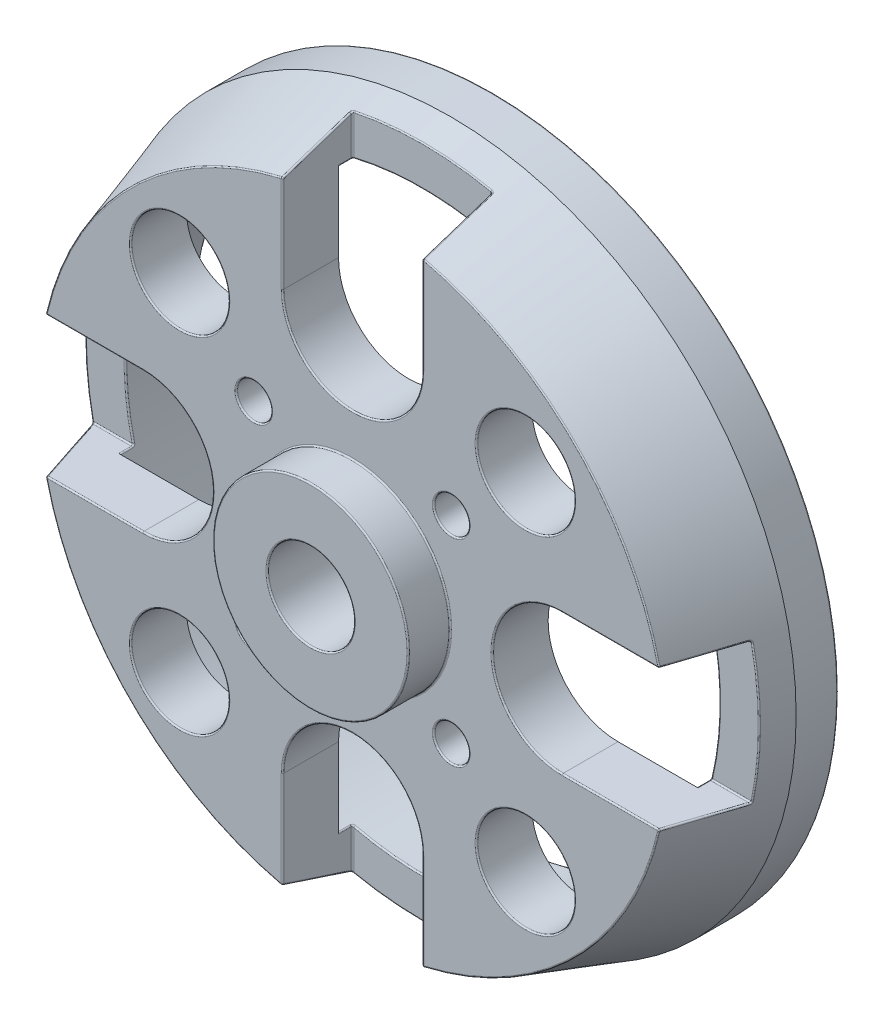
SolidWorks part; units mm, degrees
ref_plane "Спереди" through (0, 0, 0) normal (0, 0, 1) x (1, 0, 0)
ref_plane "Сверху" through (0, 0, 0) normal (0, 1, 0) x (1, 0, 0)
ref_plane "Справа" through (0, 0, 0) normal (1, 0, 0) x (0, 0, -1)
sketch "Эскиз1" plane through (0, 0, 0) normal (0, 0, 1) x (1, 0, 0)
  circle A0 centre (0, 0) radius 24.75
  dimension "D1" = 49.5
extrude "Бобышка-Вытянуть1" add sketch "Эскиз1" along normal blind 3
ref_plane "Плоскость1" through (0, 0, 10) normal (0, 0, 1) x (1, 0, 0)
sketch "Эскиз2" plane through (0, 0, 10) normal (0, 0, 1) x (1, 0, 0)
  circle A0 centre (0, 0) radius 22.5
  dimension "D1" = 45
loft "По сечениям1" add profiles "Эскиз2" section edge at (24.75, 0, 3) section "Эскиз2"
sketch "Эскиз3" plane through (0, 0, 10) normal (0, 0, 1) x (1, 0, 0)
  circle A0 centre (0, 0) radius 7
  dimension "D1" = 14
extrude "Бобышка-Вытянуть2" add sketch "Эскиз3" along normal blind 3
sketch "Эскиз4" plane through (0, 0, 10) normal (0, 0, 1) x (1, 0, 0)
  line L0 (0, 22.5) -> (0, -22.5) construction
  line L1 (-5, 15) -> (-5, 27.2025)
  line L2 (-5, 27.2025) -> (5, 27.2025)
  line L3 (5, 27.2025) -> (5, 15)
  line L4 (15, 5) -> (27.2025, 5)
  line L5 (27.2025, 5) -> (27.2025, -5)
  line L6 (27.2025, -5) -> (15, -5)
  line L7 (5, -15) -> (5, -27.2025)
  line L8 (5, -27.2025) -> (-5, -27.2025)
  line L9 (-5, -27.2025) -> (-5, -15)
  line L10 (-15, -5) -> (-27.2025, -5)
  line L11 (-27.2025, -5) -> (-27.2025, 5)
  line L12 (-27.2025, 5) -> (-15, 5)
  line L13 (-15.9099, 15.9099) -> (15.9099, -15.9099) construction
  circle A0 centre (0, 0) radius 22.5 construction
  arc A1 (-5, 15) -> (5, 15) centre (0, 15) ccw
  arc A2 (15, 5) -> (15, -5) centre (15, 0) ccw
  arc A3 (5, -15) -> (-5, -15) centre (0, -15) ccw
  arc A4 (-15, -5) -> (-15, 5) centre (-15, 0) ccw
  circle A5 centre (-12.3744, 12.3744) radius 3.5
  circle A6 centre (12.3744, 12.3744) radius 3.5
  circle A7 centre (12.3744, -12.3744) radius 3.5
  circle A8 centre (-12.3744, -12.3744) radius 3.5
  point P28 (0, 0)
  point P40 (0, 0)
  dimension "D1" = 10
  dimension "D5" = 7
  dimension "D2" = 15
  dimension "D3" = 4
  dimension "D4" = 45
  dimension "D7" = 17.5
  dimension "D6" = 4
extrude "Вырез-Вытянуть1" cut sketch "Эскиз4" against normal blind 5
sketch "Эскиз5" plane through (0, 0, 0) normal (0, 0, -1) x (-1, 0, 0)
  circle A0 centre (0, 0) radius 21.25
  dimension "D1" = 42.5
extrude "Вырез-Вытянуть2" cut sketch "Эскиз5" against normal offset from surface (6 mm away) 4 up to face at (-8.8744, -12.3744, 10)
sketch "Эскиз6" plane through (0, 0, 10) normal (0, 0, 1) x (1, 0, 0)
  line L0 (15.9099, 15.9099) -> (-15.9099, -15.9099) construction
  line L1 (-15.9099, 15.9099) -> (15.9099, -15.9099) construction
  arc A0 (21.9374, 5) -> (5, 21.9374) centre (0, 0) ccw construction
  arc A1 (-21.9374, -5) -> (-5, -21.9374) centre (0, 0) ccw construction
  arc A2 (-5, 21.9374) -> (-21.9374, 5) centre (0, 0) ccw construction
  arc A3 (5, -21.9374) -> (21.9374, -5) centre (0, 0) ccw construction
  circle A4 centre (0, 0) radius 10 construction
  dimension "D1" = 20
hole_wizard "Отверстие обработанное метчиком M3x0.51" positions "Эскиз8" profile "Эскиз7" tap size "M3x0.5" standard "Ansi Metric" end condition up to next
sketch "Эскиз8" plane through (0, 0, 10) normal (0, 0, 1) x (1, 0, 0)
  line L0 (-15.9099, 15.9099) -> (15.9099, -15.9099) construction
  line L1 (15.9099, 15.9099) -> (-15.9099, -15.9099) construction
  circle A0 centre (0, 0) radius 10 construction
  point P0 (-7.0711, 7.0711)
  point P6 (7.0711, 7.0711)
  point P10 (7.0711, -7.0711)
  point P12 (-7.0711, -7.0711)
sketch "Эскиз7" plane through (-7.0711, 7.0711, 10) normal (1, 0, 0) x (0, -1, 0)
  line L0 (0, 0) -> (0, 4)
  line L1 (0, 4) -> (1.25, 4)
  line L2 (1.25, 4) -> (1.25, 0)
  line L5 (1.25, 0) -> (0, 0)
  line L11 (0, -6.35) -> (0, 107.95) construction
  dimension "Диаметр проходного сверла" = 2.5
  dimension "Глубина проходного сверла" = 4
cosmetic thread "Отверстие резьбы1" parameters "D2"=3
cosmetic thread "Отверстие резьбы2" parameters "D2"=3
cosmetic thread "Отверстие резьбы3" parameters "D2"=3
cosmetic thread "Отверстие резьбы4" parameters "D2"=3
sketch "Эскиз9" plane through (0, 0, 13) normal (0, 0, 1) x (1, 0, 0)
  circle A0 centre (0, 0) radius 3.1
  dimension "D1" = 6.2
extrude "Вырез-Вытянуть3" cut sketch "Эскиз9" against normal through all
fillet "Скругление1" radius 0.1 61 edges at (7, 0, 10) (-10, 0, 10) (0, 10, 10) (10, 0, 10) (0, -10, 10) (-8.8744, 12.3744, 10) (15.8744, 12.3744, 10) (15.8744, -12.3744, 10) (-8.8744, -12.3744, 10) (-5.8211, -7.0711, 10) (8.3211, -7.0711, 10) (8.3211, 7.0711, 10) (-5.8211, 7.0711, 10) (24.75, 0, 0) (-21.25, 0, 0) (-20.6534, -5, 5.5) (-20.6534, 5, 5.5) (-5, 20.6534, 5.5) (5, 20.6534, 5.5) (20.6534, 5, 5.5) (20.6534, -5, 5.5) (5, -20.6534, 5.5) (-5, -20.6534, 5.5) (-22.1182, -5, 5) (-24.1071, 0, 5) (-22.1182, 5, 5) (-21.25, 0, 5) (-5, 22.1182, 5) (0, 24.1071, 5) (5, 22.1182, 5) (0, 21.25, 5) (22.1182, 5, 5) (24.1071, 0, 5) (22.1182, -5, 5) (21.25, 0, 5) (5, -22.1182, 5) (0, -24.1071, 5) (-5, -22.1182, 5) (0, -21.25, 5) (7, 0, 13) (3.1, 0, 13)
